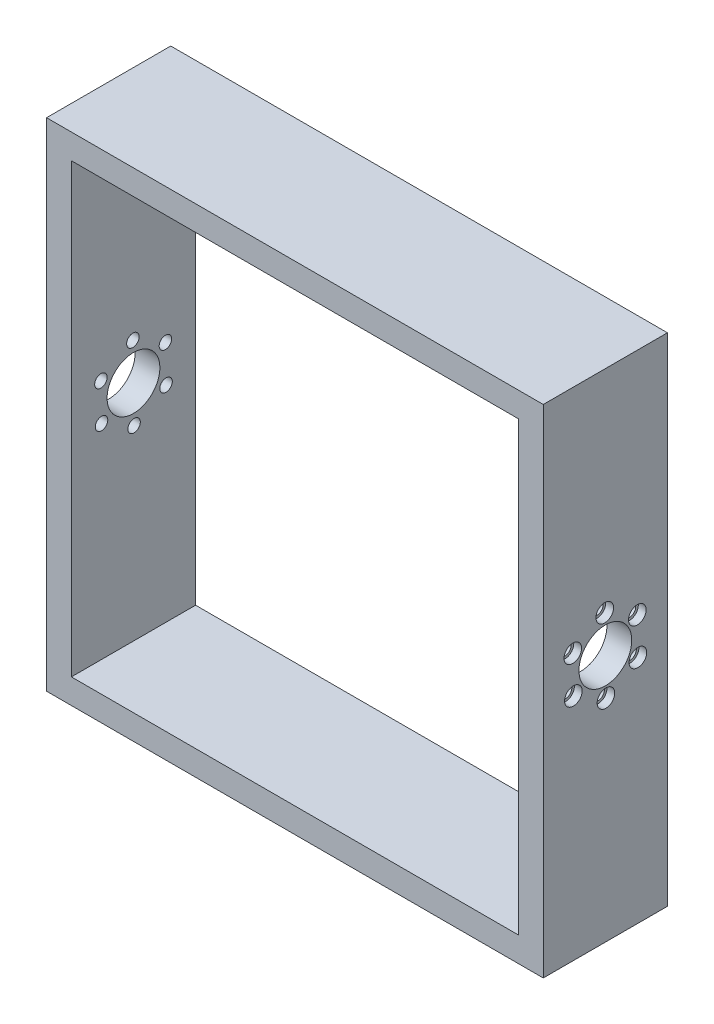
SolidWorks part; units mm, degrees
ref_plane "Front Plane" through (0, 0, 0) normal (0, 0, 1) x (1, 0, 0)
ref_plane "Top Plane" through (0, 0, 0) normal (0, 1, 0) x (1, 0, 0)
ref_plane "Right Plane" through (0, 0, 0) normal (1, 0, 0) x (0, 0, -1)
sketch "Sketch1" plane through (0, 0, 0) normal (0, 0, 1) x (1, 0, 0)
  line L0 (63.5, 0) -> (57.15, 0) construction
  line L1 (-63.5, 0) -> (63.5, 0) construction
  line L2 (0, 63.5) -> (0, -63.5)
  point P7 (0, 0)
sketch "Sketch2" plane through (0, 0, 0) normal (1, 0, 0) x (0, 0, -1)
  line L0 (76.2, 0) -> (-76.2, 0)
  point P4 (0, 0)
  dimension "Length" = 152.4
sketch "Sketch3" plane through (0, 0, 0) normal (0, 0, 1) x (1, 0, 0)
  line L0 (-63.5, 0) -> (63.5, 0) construction
  line L5 (63.5, -63.5) -> (-63.5, -63.5)
  line L6 (63.5, -63.5) -> (63.5, 63.5)
  line L11 (63.5, 63.5) -> (-63.5, 63.5)
  line L12 (-63.5, -63.5) -> (-63.5, 63.5)
  line L14 (63.5, -63.5) -> (-63.5, 63.5) construction
  line L15 (63.5, 63.5) -> (-63.5, -63.5) construction
  line L16 (57.15, -57.15) -> (-57.15, -57.15)
  line L17 (57.15, -57.15) -> (57.15, 57.15)
  line L18 (57.15, 57.15) -> (-57.15, 57.15)
  line L19 (-57.15, -57.15) -> (-57.15, 57.15)
  line L20 (57.15, -57.15) -> (-57.15, 57.15) construction
  line L21 (57.15, 57.15) -> (-57.15, -57.15) construction
  point P0 (0, 0)
  point P5 (0, 0)
  point P13 (57.15, -63.5)
  dimension "D1" = 6.35
  dimension "D3" = 127
  dimension "D4" = 127
  dimension "D2" = 6.35
extrude "Boss-Extrude1" add sketch "Sketch3" along normal up to vertex (76.2 mm away) and the other way up to vertex (76.2 mm away) up to point (0, 0, 76.2) other way up to point (0, 0, -76.2)
sketch "Sketch5" plane through (0, 0, 0) normal (1, 0, 0) x (0, 0, -1)
  line L0 (-76.2, 0) -> (76.2, 0) construction
  line L3 (-76.2, -63.5) -> (-76.2, 63.5) construction
  line L4 (76.2, -63.5) -> (76.2, 63.5) construction
  point P6 (66.675, 0)
  point P7 (114.3, 0)
  point P8 (-114.3, 0)
  point P10 (-66.675, 0)
  dimension "D1" = 142.875
  dimension "D2" = 190.5
  dimension "D3" = 142.875
  dimension "D4" = 190.5
sketch "Sketch6" plane through (0, 63.5, 0) normal (0, 1, 0) x (1, 0, 0)
  line L0 (63.5, -76.2) -> (63.5, 76.2) construction
  line L1 (-63.5, 76.2) -> (63.5, 76.2)
  line L2 (-63.5, 76.2) -> (-63.5, -44.45)
  line L3 (-63.5, -44.45) -> (63.5, -44.45)
  line L4 (63.5, 76.2) -> (63.5, -44.45)
  line L5 (63.5, -76.2) -> (-63.5, -76.2) construction
  dimension "D1" = 31.75
extrude "Cut-Extrude1" cut sketch "Sketch6" against normal through all
sketch "Sketch7" plane through (0, 63.5, 0) normal (0, 1, 0) x (1, 0, 0)
  line L0 (-63.5, -44.45) -> (63.5, -44.45) construction
  line L1 (-63.5, -76.2) -> (-63.5, -44.45) construction
  point P0 (0, -60.325)
  point P3 (0, -44.45)
  point P6 (-63.5, -60.325)
hole_wizard "M8 Clearance Hole1" positions "Sketch8" profile "Sketch9" hole size "M8" standard "ANSI Metric"
sketch "Sketch8" plane through (0, 63.5, 0) normal (0, 1, 0) x (1, 0, 0)
  point P0 (0, -60.325)
sketch "Sketch9" plane through (0, 63.5, 60.325) normal (1, 0, 0) x (0, 0, 1)
  line L0 (0, 0) -> (0, 127)
  line L1 (0, 127) -> (4.5, 127)
  line L2 (4.5, 127) -> (4.5, 0)
  line L5 (4.5, 0) -> (0, 0)
  line L11 (0, -6.35) -> (0, 107.95) construction
  dimension "Thru Hole Dia." = 9
  dimension "Thru Hole Depth" = 127
sketch "Sketch10" plane through (63.5, 0, 0) normal (1, 0, 0) x (0, 0, -1)
  line L0 (-76.2, 63.5) -> (-44.45, 63.5) construction
  line L1 (-44.45, -63.5) -> (-44.45, 63.5) construction
  point P0 (-60.325, 0)
  point P3 (-60.325, 63.5)
  point P6 (-44.45, 0)
hole_wizard "M12 Clearance Hole1" positions "Sketch11" profile "Sketch12" hole size "M12" standard "ANSI Metric" end condition through all
sketch "Sketch11" plane through (63.5, 0, 0) normal (1, 0, 0) x (0, 0, -1)
  point P0 (-60.325, 0)
sketch "Sketch12" plane through (63.5, 0, 60.325) normal (0, 1, 0) x (0, 0, -1)
  line L0 (0, 0) -> (0, 127)
  line L1 (0, 127) -> (6.75, 127)
  line L2 (6.75, 127) -> (6.75, 0)
  line L5 (6.75, 0) -> (0, 0)
  line L11 (0, -6.35) -> (0, 107.95) construction
  dimension "Thru Hole Dia." = 13.5
  dimension "Thru Hole Depth" = 127
hole_wizard "M16 Clearance Hole1" positions "Sketch13" profile "Sketch15" hole size "M16" standard "ANSI Metric"
sketch "Sketch13" plane through (0, 63.5, 0) normal (0, 1, 0) x (1, 0, 0)
  point P0 (0, -60.325)
sketch "Sketch15" plane through (0, 63.5, 60.325) normal (1, 0, 0) x (0, 0, 1)
  line L0 (0, 0) -> (0, 127)
  line L1 (0, 127) -> (8.75, 127)
  line L2 (8.75, 127) -> (8.75, 0)
  line L5 (8.75, 0) -> (0, 0)
  line L11 (0, -6.35) -> (0, 107.95) construction
  dimension "Thru Hole Dia." = 17.5
  dimension "Thru Hole Depth" = 127
hole_wizard "M16 Clearance Hole2" positions "Sketch16" profile "Sketch18" hole size "M16" standard "ANSI Metric"
sketch "Sketch16" plane through (-63.5, 0, 0) normal (-1, 0, 0) x (0, 0, 1)
  point P0 (60.325, 0)
sketch "Sketch18" plane through (-63.5, 0, 60.325) normal (0, 1, 0) x (0, 0, 1)
  line L0 (0, 0) -> (0, 11.6065)
  line L1 (0, 11.6065) -> (8.75, 6.349)
  line L2 (8.75, 6.349) -> (8.75, 0)
  line L5 (8.75, 0) -> (0, 0)
  line L10 (0, 11.6065) -> (-8.75, 6.349) construction
  line L11 (0, -6.35) -> (0, 107.95) construction
  dimension "Hole Dia." = 17.5
  dimension "Hole Depth" = 6.349
  dimension "Drill Angle" = 118
sketch "Sketch19" plane through (63.5, 0, 0) normal (1, 0, 0) x (0, 0, -1)
  point P0 (-60.4778, 9.5238)
  point P1 (-68.6492, 4.6296)
  point P3 (-68.4964, -4.8942)
  point P5 (-60.1722, -9.5238)
  point P7 (-52.0008, -4.6296)
  point P9 (-52.1536, 4.8942)
hole_wizard "CBORE for M3 SHCS1" positions "Sketch20" profile "Sketch21" counterbore size "M3" standard "ANSI Metric"
sketch "Sketch20" plane through (63.5, 0, 0) normal (1, 0, 0) x (0, 0, -1)
  point P0 (-68.4964, -4.8942)
  point P3 (-68.6492, 4.6296)
  point P6 (-60.4778, 9.5238)
  point P9 (-52.1536, 4.8942)
  point P12 (-52.0008, -4.6296)
  point P15 (-60.1722, -9.5238)
sketch "Sketch21" plane through (63.5, -4.8942, 68.4964) normal (0, 1, 0) x (0, 0, -1)
  line L0 (0, 0) -> (0, 6.35)
  line L1 (0, 6.35) -> (1.6, 6.35)
  line L3 (1.6, 6.35) -> (1.6, 2)
  line L4 (1.6, 2) -> (2.25, 2)
  line L5 (2.25, 2) -> (2.25, 0)
  line L7 (2.25, 0) -> (0, 0)
  line L11 (0, -6.35) -> (0, 107.95) construction
  dimension "Thru Hole Dia." = 3.2
  dimension "Thru Hole Depth" = 6.35
  dimension "C'Bore Dia." = 4.5
  dimension "C'Bore Depth" = 2
sketch "Sketch22" plane through (-63.5, 0, 0) normal (-1, 0, 0) x (0, 0, 1)
  point P0 (60.4778, 9.5238)
  point P1 (68.6492, 4.6296)
  point P3 (52.1536, 4.8942)
  point P5 (52.0008, -4.6296)
  point P7 (60.1722, -9.5238)
  point P9 (68.4964, -4.8942)
hole_wizard "CBORE for M3 SHCS2" positions "Sketch23" profile "Sketch24" counterbore size "M3" standard "ANSI Metric" end condition up to next
sketch "Sketch23" plane through (-63.5, 0, 0) normal (-1, 0, 0) x (0, 0, 1)
  point P0 (68.6492, 4.6296)
  point P3 (60.4778, 9.5238)
  point P6 (68.4964, -4.8942)
  point P9 (52.1536, 4.8942)
  point P12 (52.0008, -4.6296)
  point P15 (60.1722, -9.5238)
sketch "Sketch24" plane through (-63.5, 4.6296, 68.6492) normal (0, 1, 0) x (0, 0, 1)
  line L0 (0, 0) -> (0, 6.35)
  line L1 (0, 6.35) -> (1.6, 6.35)
  line L3 (1.6, 6.35) -> (1.6, 2)
  line L4 (1.6, 2) -> (2.25, 2)
  line L5 (2.25, 2) -> (2.25, 0)
  line L7 (2.25, 0) -> (0, 0)
  line L11 (0, -6.35) -> (0, 107.95) construction
  dimension "Thru Hole Dia." = 3.2
  dimension "Thru Hole Depth" = 6.35
  dimension "C'Bore Dia." = 4.5
  dimension "C'Bore Depth" = 2
equation "\"D1@Sketch3\"=\"Wall thickness@Sketch1\""
equation "\"D1@Sketch5\"=\"Width@Sketch1\"*1.125"
equation "\"D2@Sketch5\"=\"Width@Sketch1\"*1.5"
equation "\"D3@Sketch5\"=\"D1@Sketch5\""
equation "\"D4@Sketch5\"=\"D2@Sketch5\""
equation "\"D2@Sketch3\"=\"Wall Thickness@Sketch1\""
